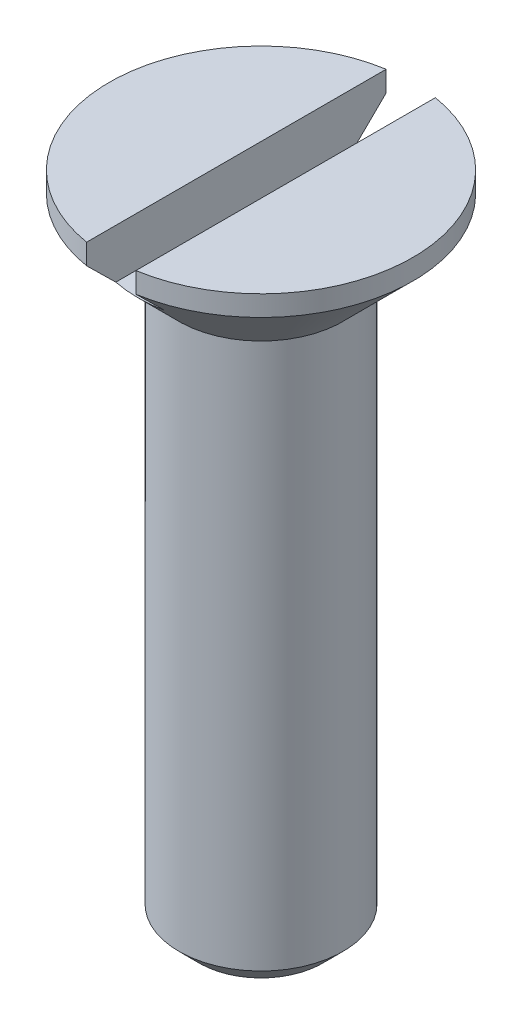
SolidWorks part; units mm, degrees
ref_plane "Спереди" through (0, 0, 0) normal (0, 0, 1) x (1, 0, 0)
ref_plane "Сверху" through (0, 0, 0) normal (0, 1, 0) x (1, 0, 0)
ref_plane "Справа" through (0, 0, 0) normal (1, 0, 0) x (0, 0, -1)
sketch "Эскиз1" plane through (0, 0, 0) normal (0, 0, 1) x (1, 0, 0)
  line L0 (0, 0) -> (-1.5, 0)
  line L1 (-1.5, 0) -> (-2, 0.5)
  line L2 (-2, 0.5) -> (-2, 13.8)
  line L3 (-2, 13.8) -> (-3.7, 15.5)
  line L4 (-3.7, 15.5) -> (-3.7, 16)
  line L5 (-3.7, 16) -> (0, 16)
  line L6 (0, 16) -> (0, 0)
  dimension "D1" = 2
  dimension "D2" = 45
  dimension "D3" = 1.5
  dimension "D4" = 16
  dimension "D5" = 45
  dimension "D6" = 2.2
  dimension "D7" = 3.7
revolve "Повернуть1" add sketch "Эскиз1" angle 360 about L6
sketch "Эскиз2" plane through (0, 0, 0) normal (0, 0, 1) x (1, 0, 0)
  line L0 (0, 0) -> (0, 16) construction
  line L1 (3.7, 16) -> (-3.7, 16) construction
  line L3 (-0.6, 16) -> (0.6, 16)
  line L4 (-0.6, 16) -> (-0.6, 14.8)
  line L5 (-0.6, 14.8) -> (0.6, 14.8)
  line L6 (0.6, 16) -> (0.6, 14.8)
  dimension "D1" = 1.2
  dimension "D2" = 1.2
extrude "Вырез-Вытянуть1" cut sketch "Эскиз2" against normal through all and the other way through all
